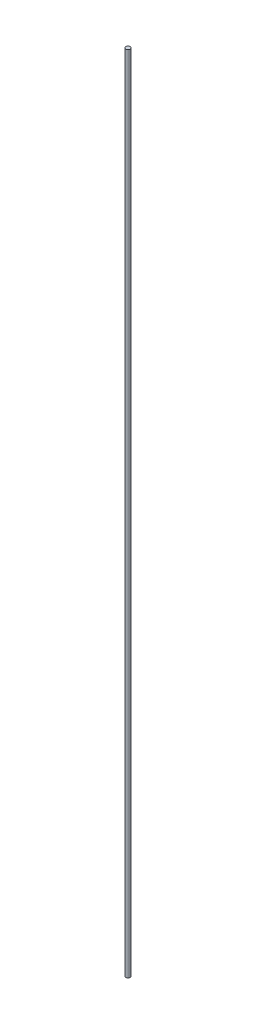
SolidWorks part; units mm, degrees
ref_plane "Front Plane" through (0, 0, 0) normal (0, 0, 1) x (1, 0, 0)
ref_plane "Top Plane" through (0, 0, 0) normal (0, 1, 0) x (1, 0, 0)
ref_plane "Right Plane" through (0, 0, 0) normal (1, 0, 0) x (0, 0, -1)
sketch "Sketch1" plane through (0, 0, 0) normal (0, 1, 0) x (1, 0, 0)
  circle A0 centre (0, 0) radius 0.1
extrude "Boss-Extrude1" add sketch "Sketch1" along normal blind 36
